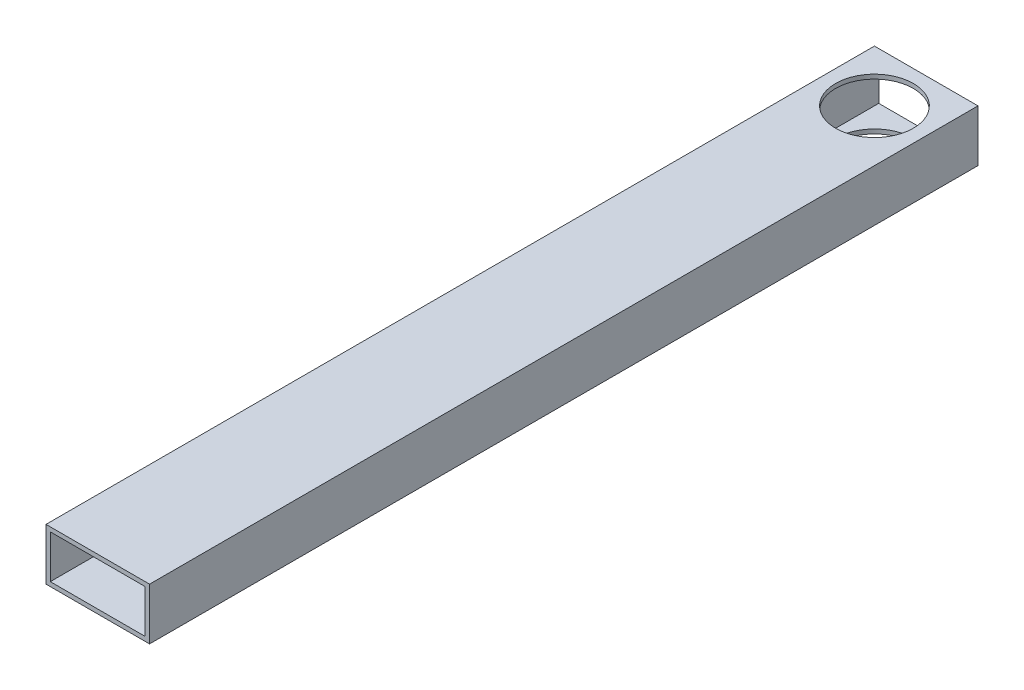
SolidWorks part; units mm, degrees
ref_plane "Front Plane" through (0, 0, 0) normal (0, 0, 1) x (1, 0, 0)
ref_plane "Top Plane" through (0, 0, 0) normal (0, 1, 0) x (1, 0, 0)
ref_plane "Right Plane" through (0, 0, 0) normal (1, 0, 0) x (0, 0, -1)
sketch "Sketch1" plane through (0, 0, 0) normal (0, 0, 1) x (1, 0, 0)
  line L1 (0, 0) -> (38.1, 0)
  line L2 (0, 0) -> (0, 19.05)
  line L3 (0, 19.05) -> (38.1, 19.05)
  line L4 (38.1, 0) -> (38.1, 19.05)
  dimension "D1" = 19.05
  dimension "D2" = 38.1
extrude "Extrude-Thin1" add sketch "Sketch1" along normal blind 304.8 thin thin type one direction reverse wall 1.5875
sketch "Sketch3" plane through (0, 0, 0) normal (0, -1, 0) x (1, 0, 0)
  line L0 (0, 304.8) -> (0, 0) construction
  line L1 (0, 0) -> (38.1, 0) construction
  circle A0 centre (19.05, 19.05) radius 14.2875
  dimension "D1" = 19.05
  dimension "D2" = 28.575
  dimension "D3" = 19.05
extrude "Cut-Extrude2" cut sketch "Sketch3" against normal through all
